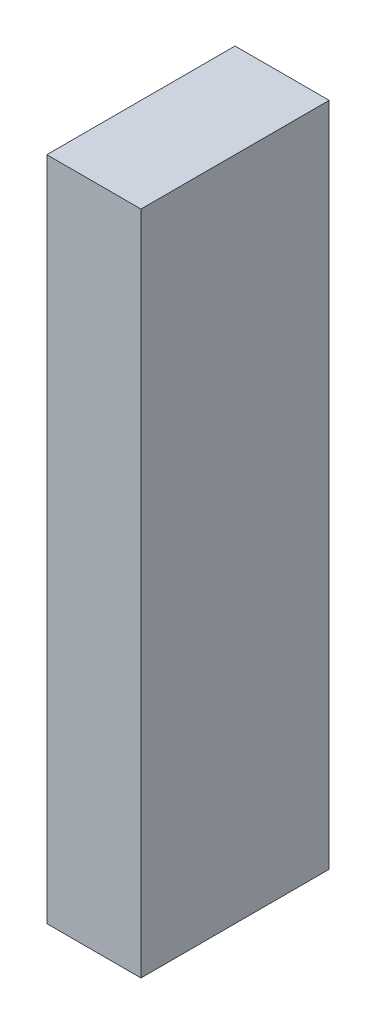
SolidWorks part; units mm, degrees
ref_plane "Front Plane" through (0, 0, 0) normal (0, 0, 1) x (1, 0, 0)
ref_plane "Top Plane" through (0, 0, 0) normal (0, 1, 0) x (1, 0, 0)
ref_plane "Right Plane" through (0, 0, 0) normal (1, 0, 0) x (0, 0, -1)
sketch "Sketch1" plane through (0, 0, 0) normal (0, 1, 0) x (1, 0, 0)
  line L0 (-25.4, 50.8) -> (25.4, -50.8) construction
  line L1 (-25.4, -50.8) -> (25.4, -50.8)
  line L2 (-25.4, -50.8) -> (-25.4, 50.8)
  line L3 (-25.4, 50.8) -> (25.4, 50.8)
  line L4 (25.4, -50.8) -> (25.4, 50.8)
  line L5 (-25.4, -50.8) -> (25.4, 50.8) construction
  dimension "D1" = 50.8
  dimension "D2" = 101.6
extrude "Boss-Extrude1" add sketch "Sketch1" along normal blind 359.41
